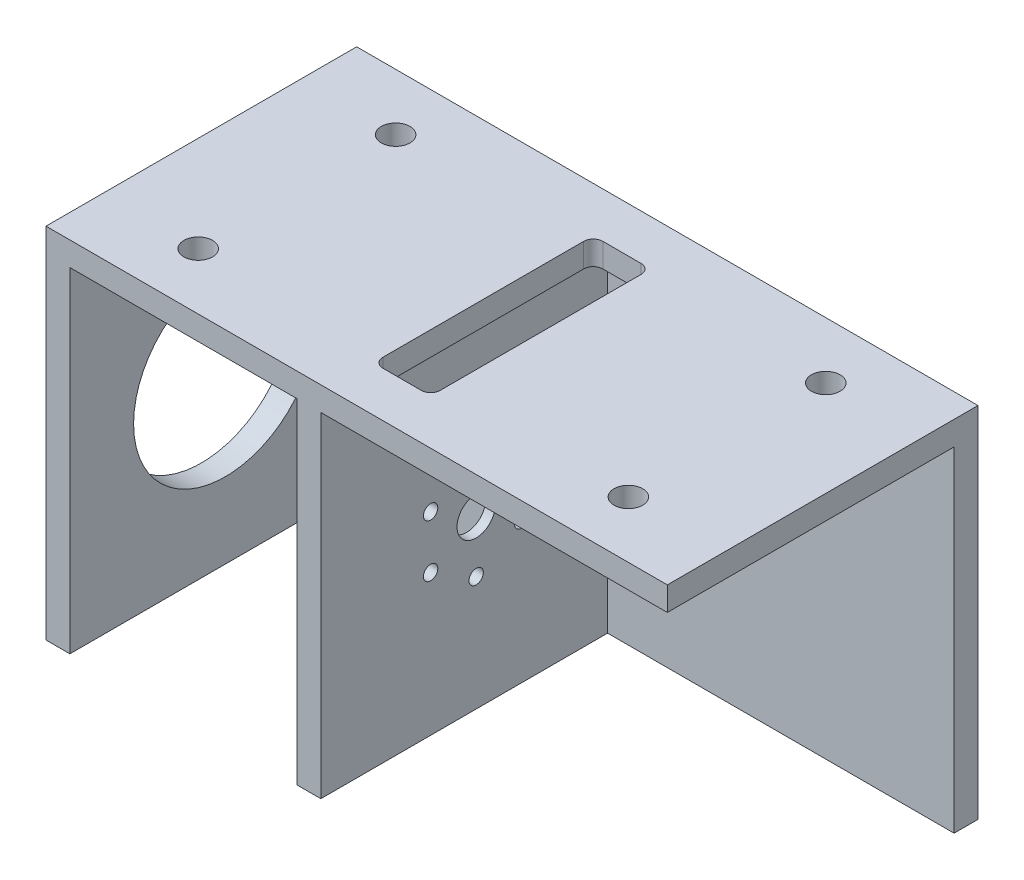
SolidWorks part; units mm, degrees
ref_plane "Front Plane" through (0, 0, 0) normal (0, 0, 1) x (1, 0, 0)
ref_plane "Top Plane" through (0, 0, 0) normal (0, 1, 0) x (1, 0, 0)
ref_plane "Right Plane" through (0, 0, 0) normal (1, 0, 0) x (0, 0, -1)
sketch "Sketch1" plane through (0, 0, 0) normal (0, 1, 0) x (1, 0, 0)
  line L0 (0, 18.2197) -> (0, -18.3609) construction
  line L1 (-19.3496, 0) -> (20.197, 0) construction
  line L2 (-45, 0) -> (-45, -10) construction
  line L3 (65, 32.5) -> (-65, 32.5)
  line L4 (-65, 32.5) -> (-65, -32.5)
  line L5 (65, -32.5) -> (-65, -32.5)
  line L6 (65, 32.5) -> (65, -32.5)
  line L7 (6, 23) -> (-6, 23)
  line L8 (-6, 23) -> (-6, -23)
  line L9 (6, -23) -> (-6, -23)
  line L10 (6, 23) -> (6, -23)
  circle A0 centre (-45, 0) radius 10 construction
  circle A6 centre (-45, 20.65) radius 3
  circle A7 centre (-45, 20.65) radius 3.4 construction
  circle A8 centre (-45, -20.65) radius 3
  circle A9 centre (-45, -20.65) radius 3.4 construction
  circle A10 centre (45, 20.65) radius 3
  circle A11 centre (45, 20.65) radius 3.4 construction
  circle A12 centre (45, 0) radius 10 construction
  circle A13 centre (45, -20.65) radius 3.4 construction
  circle A14 centre (45, -20.65) radius 3
  point P18 (-65, 0)
  point P20 (0, 32.5)
  point P21 (0, -32.5)
  point P33 (-6, 0)
  point P35 (0, -23)
  point P36 (0, 23)
  dimension "D1" = 20
  dimension "D3" = 6.8
  dimension "D4" = 41.3
  dimension "D5" = 90
  dimension "D2" = 6
  dimension "D6" = 130
  dimension "D7" = 65
  dimension "D8" = 12
  dimension "D9" = 46
extrude "Boss-Extrude1" add sketch "Sketch1" along normal blind 5
fillet "Fillet1" radius 2 4 edges at (6, 2.5, 23) (-6, 2.5, 23) (6, 2.5, -23) (-6, 2.5, -23)
sketch "Sketch2" plane through (0, 0, 0) normal (0, -1, 0) x (1, 0, 0)
  line L0 (-65, -32.5) -> (-65, -27.5)
  line L1 (-65, -32.5) -> (-65, 32.5) construction
  line L2 (-65, -27.5) -> (65, -27.5)
  line L3 (65, 32.5) -> (65, -32.5) construction
  line L4 (65, -27.5) -> (65, -32.5)
  line L5 (65, -32.5) -> (-65, -32.5)
  dimension "D1" = 5
extrude "Boss-Extrude2" add sketch "Sketch2" along normal blind 70
sketch "Sketch3" plane through (0, 0, -27.5) normal (0, 0, 1) x (1, 0, 0)
  line L0 (0, 0) -> (0, -70) construction
  line L1 (65, 0) -> (-65, 0) construction
  line L2 (65, -70) -> (-65, -70) construction
  line L3 (0, -35) -> (-65, -35) construction
  line L4 (-65, -70) -> (-65, 0) construction
  line L5 (0, -35) -> (65, -35) construction
  line L6 (65, -70) -> (65, 0) construction
  line L7 (-10, 0) -> (-10, -70) construction
  line L8 (32.5, 0) -> (32.5, -70) construction
  line L9 (-7.5, 0) -> (-12.5, 0)
  line L10 (-12.5, 0) -> (-12.5, -70)
  line L11 (-12.5, -70) -> (-7.5, -70)
  line L12 (-7.5, 0) -> (-7.5, -70)
  point P18 (32.5, -35)
  dimension "D1" = 5
  dimension "D2" = 10
extrude "Boss-Extrude3" add sketch "Sketch3" along normal up to surface (60 mm away) up to face at (0, 2.5, 32.5)
sketch "Sketch4" plane through (-12.5, 0, 0) normal (-1, 0, 0) x (0, 0, 1)
  line L0 (0, 0) -> (0, -70) construction
  line L1 (32.5, -70) -> (-27.5, -70) construction
  line L2 (-27.5, -35) -> (32.5, -35) construction
  line L4 (-27.5, 0) -> (-27.5, -70) construction
  line L5 (32.5, 0) -> (32.5, -70) construction
  circle A0 centre (0, -35) radius 4
  circle A1 centre (0, -35) radius 11 construction
  circle A2 centre (0, -24) radius 1.5
  circle A3 centre (-9.5263, -29.5) radius 1.5
  circle A4 centre (-9.5263, -40.5) radius 1.5
  circle A5 centre (0, -46) radius 1.5
  circle A6 centre (9.5263, -40.5) radius 1.5
  circle A7 centre (9.5263, -29.5) radius 1.5
  point P28 (0, -35)
  dimension "D1" = 8
  dimension "D2" = 22
  dimension "D3" = 3
  dimension "D4" = 6
extrude "Cut-Extrude1" cut sketch "Sketch4" against normal blind 10
sketch "Sketch5" plane through (-12.5, 0, 0) normal (-1, 0, 0) x (0, 0, 1)
  circle A0 centre (0, -35) radius 8.5
  dimension "D1" = 17
extrude "Cut-Extrude2" cut sketch "Sketch5" against normal blind 3
sketch "Sketch6" plane through (0, 0, -27.5) normal (0, 0, 1) x (1, 0, 0)
  line L0 (-12.5, -70) -> (-65, -70) construction
  line L1 (-65, 0) -> (-60, 0)
  line L2 (-65, 0) -> (-65, -70)
  line L3 (-65, -70) -> (-60, -70)
  line L4 (-60, 0) -> (-60, -70)
  dimension "D1" = 5
extrude "Boss-Extrude4" add sketch "Sketch6" along normal up to surface (60 mm away) up to face at (-5, -16.25, 32.5)
sketch "Sketch7" plane through (-65, 0, 0) normal (-1, 0, 0) x (0, 0, 1)
  line L0 (0, 5) -> (0, -70) construction
  line L1 (-32.5, 5) -> (32.5, 5) construction
  line L2 (32.5, -70) -> (-32.5, -70) construction
  line L3 (32.5, 0) -> (-32.5, 0) construction
  line L4 (32.5, 5) -> (32.5, -70) construction
  line L5 (-32.5, 5) -> (-32.5, -70) construction
  line L6 (-32.5, 0) -> (-32.5, -70) construction
  line L7 (-32.5, -35) -> (32.5, -35) construction
  circle A0 centre (0, -35) radius 19.175
  dimension "D1" = 38.35
extrude "Cut-Extrude3" cut sketch "Sketch7" against normal up to surface (5 mm away) up to face at (-60, -35, 2.5)
